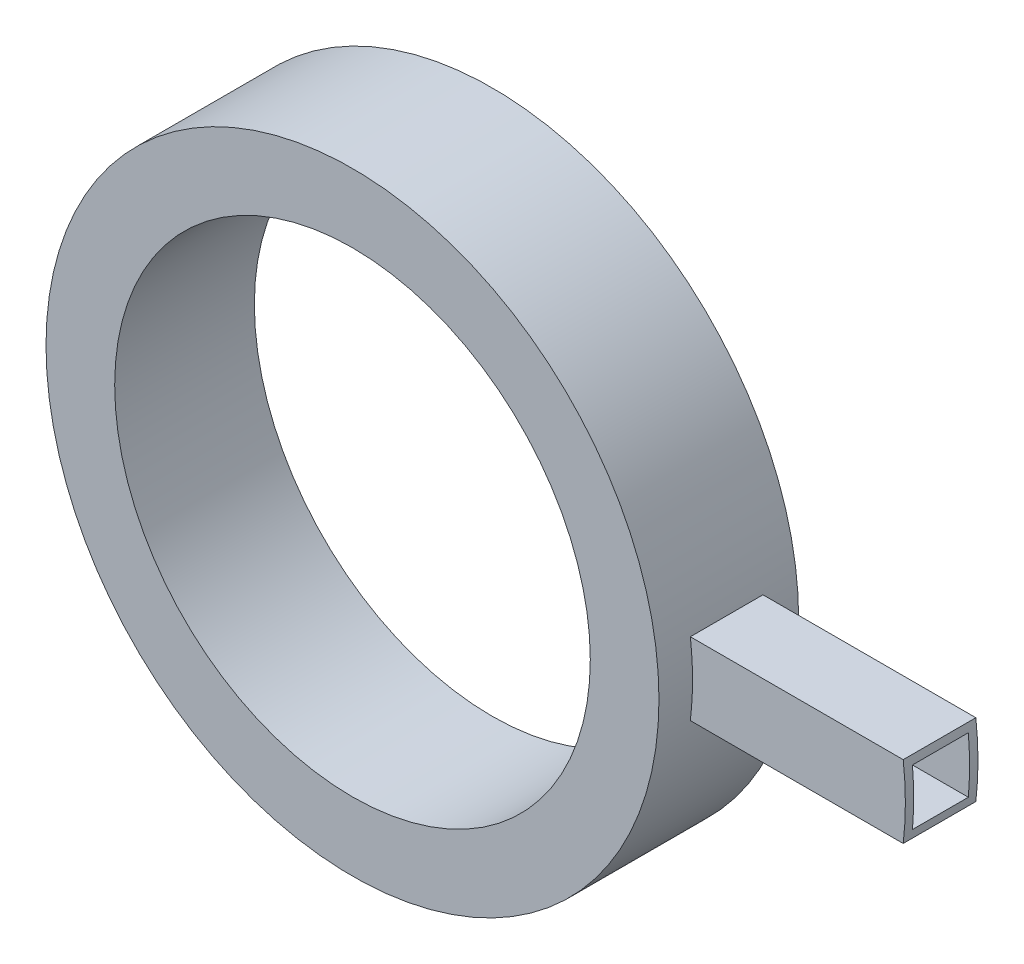
SolidWorks part; units mm, degrees
ref_plane "Front Plane" through (0, 0, 0) normal (0, 0, 1) x (1, 0, 0)
ref_plane "Top Plane" through (0, 0, 0) normal (0, 1, 0) x (1, 0, 0)
ref_plane "Right Plane" through (0, 0, 0) normal (1, 0, 0) x (0, 0, -1)
sketch "Sketch1" plane through (0, 0, 0) normal (0, 0, 1) x (1, 0, 0)
  circle A0 centre (0, 0) radius 85.1309
  circle A1 centre (0, 0) radius 109.7143
extrude "Boss-Extrude1" add sketch "Sketch1" along normal blind 50
sketch "Sketch2" plane through (0, 0, 0) normal (1, 0, 0) x (0, 0, -1)
  line L1 (-35, 10) -> (-15, 10)
  line L2 (-35, 10) -> (-35, -10)
  line L3 (-35, -10) -> (-15, -10)
  line L4 (-15, 10) -> (-15, -10)
  line L6 (-38, 13) -> (-12, 13)
  line L7 (-12, 13) -> (-12, -13)
  line L8 (-38, -13) -> (-12, -13)
  line L9 (-38, 13) -> (-38, -13)
  point P4 (-15, 0)
  point P8 (-25, 10)
  dimension "D1" = 3
extrude "Boss-Extrude2" add sketch "Sketch2" along normal blind 76.2 from surface starting at face at (109.7143, 0, 50)
